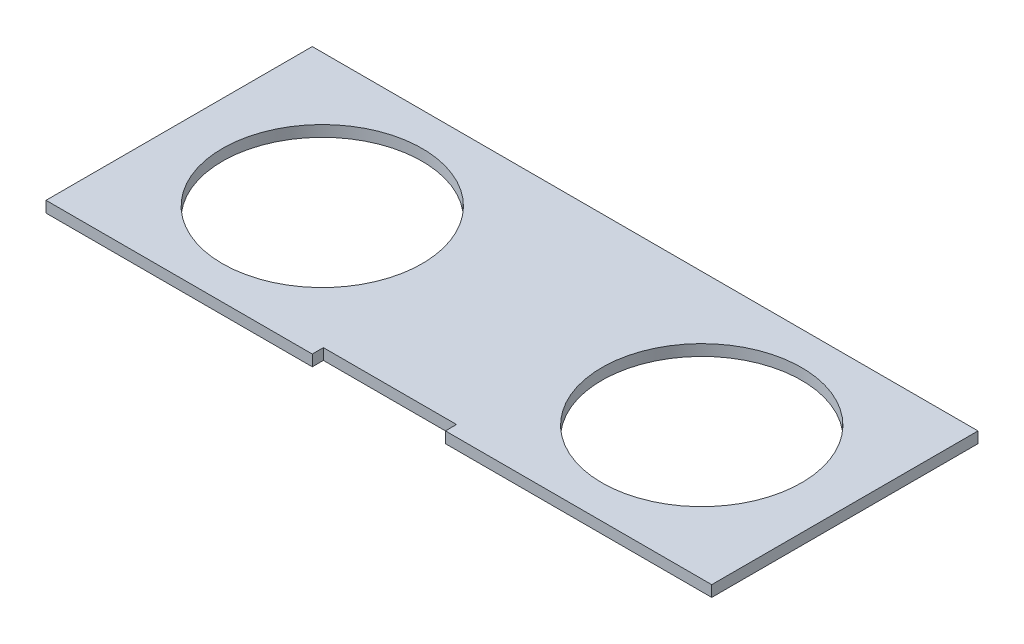
SolidWorks part; units mm, degrees
ref_plane "Front Plane" through (0, 0, 0) normal (0, 0, 1) x (1, 0, 0)
ref_plane "Top Plane" through (0, 0, 0) normal (0, 1, 0) x (1, 0, 0)
ref_plane "Right Plane" through (0, 0, 0) normal (1, 0, 0) x (0, 0, -1)
sketch "Sketch1" plane through (0, 0, 0) normal (0, 1, 0) x (1, 0, 0)
  line L1 (-300, 120) -> (0, 120)
  line L2 (-300, 120) -> (-300, 0)
  line L3 (-300, 0) -> (0, 0)
  line L4 (0, 120) -> (0, 0)
  dimension "D1" = 300
  dimension "D2" = 120
extrude "Boss-Extrude1" add sketch "Sketch1" along normal blind 5
sketch "Sketch2" plane through (0, 5, 0) normal (0, 1, 0) x (1, 0, 0)
  line L9 (0, 0) -> (0, 120) construction
  line L11 (-300, 0) -> (0, 0) construction
  line L12 (-120, 0) -> (-180, 0)
  line L13 (-120, 0) -> (-120, 5)
  line L14 (-120, 5) -> (-180, 5)
  line L15 (-180, 0) -> (-180, 5)
  line L16 (0, 120) -> (-300, 120) construction
  line L17 (-300, 120) -> (-300, 0) construction
  circle A0 centre (-64.5, 60) radius 45
  circle A1 centre (-235.5, 60) radius 45
  dimension "D2" = 90
  dimension "D3" = 90
  dimension "D6" = 64.5
  dimension "D7" = 64.5
  dimension "D4" = 60
  dimension "D5" = 60
  dimension "D9" = 60
  dimension "D10" = 120
  dimension "D11" = 5
extrude "Cut-Extrude1" cut sketch "Sketch2" against normal blind 5
